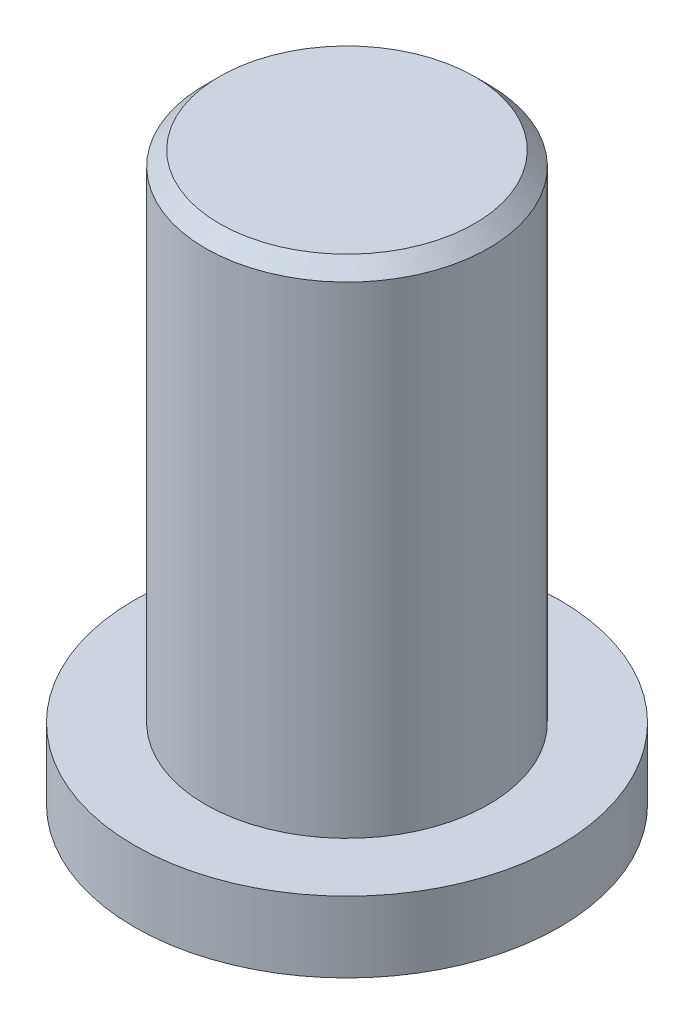
SolidWorks part; units mm, degrees
ref_plane "Front Plane" through (0, 0, 0) normal (0, 0, 1) x (1, 0, 0)
ref_plane "Top Plane" through (0, 0, 0) normal (0, 1, 0) x (1, 0, 0)
ref_plane "Right Plane" through (0, 0, 0) normal (1, 0, 0) x (0, 0, -1)
sketch "Sketch1" plane through (0, 0, 0) normal (0, 1, 0) x (1, 0, 0)
  circle A0 centre (0, 0) radius 15
  dimension "D1" = 30
extrude "Boss-Extrude1" add sketch "Sketch1" along normal blind 5
sketch "Sketch2" plane through (0, 5, 0) normal (0, 1, 0) x (1, 0, 0)
  circle A0 centre (0, 0) radius 10
  dimension "D1" = 20
extrude "Boss-Extrude2" add sketch "Sketch2" along normal blind 35
chamfer "Chamfer1" distance 1 angle 45 1 edges at (0, 40, 10)
